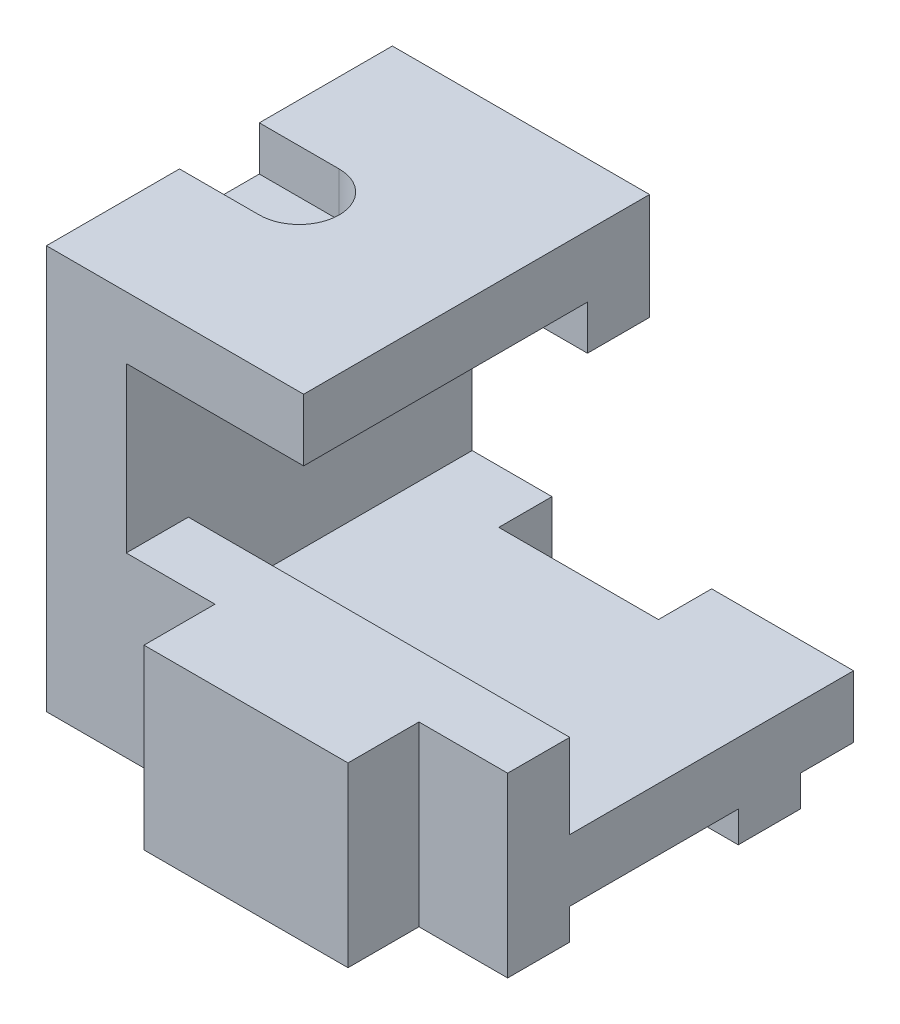
SolidWorks part; units mm, degrees
ref_plane "Спереди" through (0, 0, 0) normal (0, 0, 1) x (1, 0, 0)
ref_plane "Сверху" through (0, 0, 0) normal (0, 1, 0) x (1, 0, 0)
ref_plane "Справа" through (0, 0, 0) normal (1, 0, 0) x (0, 0, -1)
sketch "Эскиз1" plane through (0, 0, 0) normal (0, 0, 1) x (1, 0, 0)
  line L1 (0, 0) -> (50, 0)
  line L2 (0, 0) -> (0, -7)
  line L3 (0, -7) -> (50, -7)
  line L4 (50, 0) -> (50, -7)
  line L5 (0, 0) -> (7, 0)
  line L6 (0, 0) -> (0, 35)
  line L7 (0, 35) -> (7, 35)
  line L8 (7, 0) -> (7, 35)
  line L9 (7, 35) -> (27, 35)
  line L10 (7, 35) -> (7, 28)
  line L11 (7, 28) -> (27, 28)
  line L12 (27, 35) -> (27, 28)
  dimension "D1" = 50
  dimension "D2" = 7
  dimension "D3" = 35
  dimension "D4" = 20
extrude "Бобышка-Вытянуть1" add sketch "Эскиз1" along normal blind 39 contours L12 L9 L8 L11 | L1 L8 L7 L6 | L4 L1 L2 L3
sketch "Эскиз2" plane through (0, 35, 0) normal (0, 1, 0) x (1, 0, 0)
  line L0 (0, -19.5) -> (27, -19.5) construction
  line L1 (0, -39) -> (0, 0) construction
  line L2 (27, -39) -> (27, 0) construction
  line L3 (7, -39) -> (7, 0) construction
  line L4 (7, -15) -> (0, -15)
  line L5 (0, -15) -> (0, -24)
  line L6 (0, -24) -> (7, -24)
  circle A0 centre (7, -19.5) radius 4.5
  line M2 (0, 0) -> (0, -39)
  dimension "D1" = 9
extrude "Вырез-Вытянуть1" cut sketch "Эскиз2" against normal blind 5 contours A0 L0 | L0 A0 | L0 A0 L4 M2 | L0 L5 L6 A0
sketch "Эскиз3" plane through (27, 0, 0) normal (1, 0, 0) x (0, 0, -1)
  line L0 (0, 35) -> (0, 28) construction
  line L1 (0, 28) -> (-7, 28)
  line L2 (0, 28) -> (0, 23)
  line L3 (0, 23) -> (-7, 23)
  line L4 (-7, 28) -> (-7, 23)
  dimension "D2" = 5
extrude "Бобышка-Вытянуть2" add sketch "Эскиз3" against normal up to next
sketch "Эскиз4" plane through (50, 0, 0) normal (1, 0, 0) x (0, 0, -1)
  line L0 (-39, -3.5) -> (0, -3.5) construction
  line L1 (-39, 0) -> (-39, -7) construction
  line L2 (0, 0) -> (0, -7) construction
  line L3 (-39, 0) -> (-39, 28) construction
  line L4 (-39, -10.5) -> (-32, -10.5)
  line L5 (-39, -10.5) -> (-39, 3.5)
  line L6 (-39, 3.5) -> (-32, 3.5)
  line L7 (-32, -10.5) -> (-32, 3.5)
  line L8 (-39, -10.5) -> (-32, 3.5) construction
  line L9 (-39, 3.5) -> (-32, -10.5) construction
  line L10 (-39, -7) -> (0, -7) construction
  line L11 (-13, -7) -> (-6, -7)
  line L12 (-13, -7) -> (-13, -10.5)
  line L13 (-13, -10.5) -> (-6, -10.5)
  line L14 (-6, -7) -> (-6, -10.5)
  point P6 (-35.5, -3.5)
  dimension "D1" = 14
  dimension "D2" = 6
extrude "Бобышка-Вытянуть3" add sketch "Эскиз4" against normal up to surface (50 mm away) up to face at (0, 23.25, 19.5)
sketch "Эскиз5" plane through (0, -7, 0) normal (0, -1, 0) x (1, 0, 0)
  line L0 (25, 0) -> (25, 39) construction
  line L1 (0, 0) -> (50, 0) construction
  line L2 (0, 39) -> (50, 39) construction
  line L4 (34, 0) -> (16, 0)
  line L5 (34, 0) -> (34, 6)
  line L6 (34, 6) -> (16, 6)
  line L7 (16, 0) -> (16, 6)
  line L8 (34, 0) -> (16, 6) construction
  line L9 (34, 6) -> (16, 0) construction
  point P6 (25, 3)
  dimension "D1" = 6
  dimension "D2" = 18
extrude "Вырез-Вытянуть2" cut sketch "Эскиз5" against normal up to next
sketch "Эскиз6" plane through (0, 0, 39) normal (0, 0, 1) x (1, 0, 0)
  line L0 (28.5, 3.5) -> (28.5, -10.5) construction
  line L1 (7, 3.5) -> (50, 3.5) construction
  line L2 (0, -10.5) -> (50, -10.5) construction
  line L4 (17, -10.5) -> (40, -10.5)
  line L5 (17, -10.5) -> (17, 3.5)
  line L6 (17, 3.5) -> (40, 3.5)
  line L7 (40, -10.5) -> (40, 3.5)
  line L8 (17, -10.5) -> (40, 3.5) construction
  line L9 (17, 3.5) -> (40, -10.5) construction
  point P6 (28.5, -3.5)
  dimension "D1" = 23
extrude "Бобышка-Вытянуть4" add sketch "Эскиз6" along normal blind 8
sketch "Эскиз7" plane through (0, 0, 0) normal (-1, 0, 0) x (0, 0, 1)
  line L14 (39, -10.5) -> (39, 35)
  line L15 (39, 35) -> (24, 35)
  line L16 (24, 35) -> (24, 30)
  line L17 (24, 30) -> (15, 30)
  line L18 (15, 30) -> (15, 35)
  line L19 (15, 35) -> (0, 35)
  line L20 (0, 35) -> (0, -7)
  line L21 (0, -7) -> (6, -7)
  line L22 (6, -7) -> (6, -10.5)
  line L23 (6, -10.5) -> (13, -10.5)
  line L24 (13, -10.5) -> (13, -7)
  line L25 (13, -7) -> (32, -7)
  line L26 (32, -7) -> (32, -10.5)
  line L27 (32, -10.5) -> (39, -10.5)
  line L28 (39, -10.5) -> (39, 35)
  line L29 (39, 35) -> (24, 35)
  line L30 (24, 35) -> (24, 30)
  line L31 (24, 30) -> (15, 30)
  line L32 (15, 30) -> (15, 35)
  line L33 (15, 35) -> (0, 35)
  line L34 (0, 35) -> (0, -7)
  line L35 (0, -7) -> (6, -7)
  line L36 (6, -7) -> (6, -10.5)
  line L37 (6, -10.5) -> (13, -10.5)
  line L38 (13, -10.5) -> (13, -7)
  line L39 (13, -7) -> (32, -7)
  line L40 (32, -7) -> (32, -10.5)
  line L41 (32, -10.5) -> (39, -10.5)
  dimension "D1" = 0
extrude "Бобышка-Вытянуть5" add sketch "Эскиз7" along normal blind 2
sketch "Эскиз8" plane through (0, 3.5, 0) normal (0, 1, 0) x (1, 0, 0)
  line L8 (7, -32) -> (7, -39)
  line L9 (7, -39) -> (17, -39)
  line L10 (17, -39) -> (17, -47)
  line L11 (17, -47) -> (40, -47)
  line L12 (40, -47) -> (40, -39)
  line L13 (40, -39) -> (50, -39)
  line L14 (50, -39) -> (50, -32)
  line L15 (50, -32) -> (7, -32)
  line L16 (7, -32) -> (7, -39)
  line L17 (7, -39) -> (17, -39)
  line L18 (17, -39) -> (17, -47)
  line L19 (17, -47) -> (40, -47)
  line L20 (40, -47) -> (40, -39)
  line L21 (40, -39) -> (50, -39)
  line L22 (50, -39) -> (50, -32)
  line L23 (50, -32) -> (7, -32)
  dimension "D1" = 0
extrude "Бобышка-Вытянуть6" add sketch "Эскиз8" along normal blind 6
